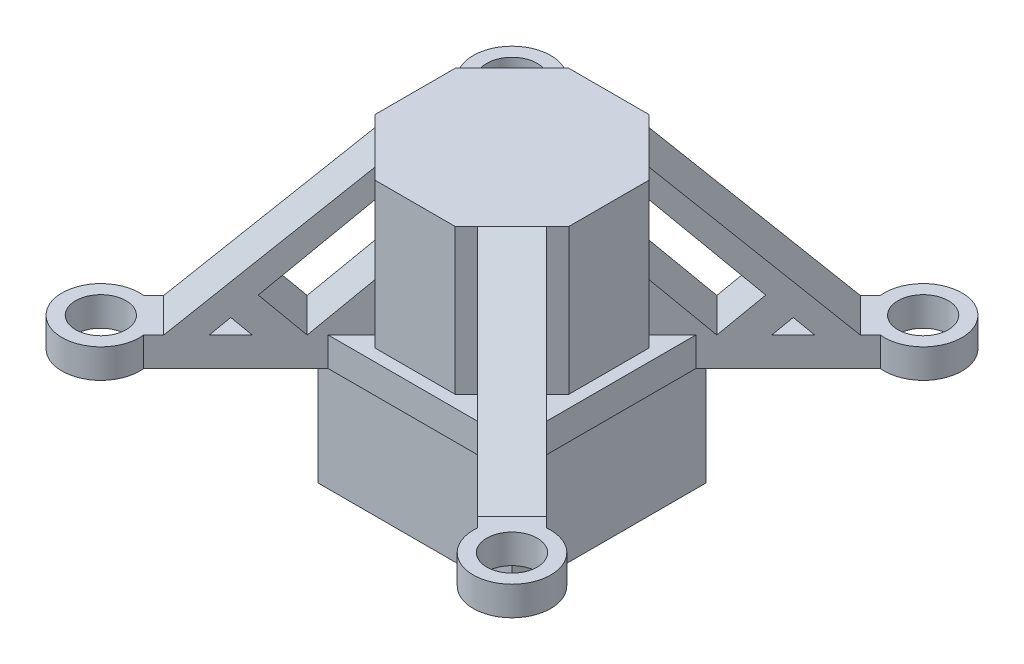
SolidWorks part; units mm, degrees
ref_plane "Front Plane" through (0, 0, 0) normal (0, 0, 1) x (1, 0, 0)
ref_plane "Top Plane" through (0, 0, 0) normal (0, 1, 0) x (1, 0, 0)
ref_plane "Right Plane" through (0, 0, 0) normal (1, 0, 0) x (0, 0, -1)
sketch "Sketch1" plane through (0, 0, 0) normal (0, 1, 0) x (1, 0, 0)
  line L1 (-10, 10) -> (10, 10)
  line L2 (-10, 10) -> (-10, -10)
  line L3 (-10, -10) -> (10, -10)
  line L4 (10, 10) -> (10, -10)
  line L5 (-10, 10) -> (10, -10) construction
  line L6 (-10, -10) -> (10, 10) construction
  point P0 (0, 0)
extrude "Boss-Extrude1" add sketch "Sketch1" against normal blind 12
sketch "Sketch2" plane through (0, 0, 0) normal (0, 1, 0) x (1, 0, 0)
  line L0 (7.7145, -11.25) -> (17.2375, -20.773)
  line L1 (11.25, 7.7145) -> (20.773, 17.2375)
  line L2 (7.7145, 11.25) -> (17.2375, 20.773)
  line L3 (11.25, -7.7145) -> (20.773, -17.2375)
  line L4 (-11.25, -7.7145) -> (-20.773, -17.2375)
  line L5 (-7.7145, -11.25) -> (-17.2375, -20.773)
  line L6 (-7.7145, 11.25) -> (-17.2375, 20.773)
  line L7 (-11.25, 7.7145) -> (-20.773, 17.2375)
  line L9 (-7.7145, -11.25) -> (7.7145, -11.25)
  line L10 (-11.25, -7.7145) -> (-11.25, 7.7145)
  line L11 (-7.7145, 11.25) -> (7.7145, 11.25)
  line L12 (11.25, -7.7145) -> (11.25, 7.7145)
  arc A0 (20.773, 17.2375) -> (17.2375, 20.773) centre (21.2132, 21.2132) ccw
  arc A1 (17.2375, -20.773) -> (20.773, -17.2375) centre (21.2132, -21.2132) ccw
  arc A2 (-20.773, -17.2375) -> (-17.2375, -20.773) centre (-21.2132, -21.2132) ccw
  arc A3 (-17.2375, 20.773) -> (-20.773, 17.2375) centre (-21.2132, 21.2132) ccw
  point P4 (0, 0)
  point P24 (0, 0)
  dimension "D1" = 4
extrude "Boss-Extrude2" add sketch "Sketch2" along normal blind 3
ref_plane "Plane1" through (0, 3, 0) normal (0, 1, 0) x (1, 0, 0)
sketch "Sketch3" plane through (0, 3, 0) normal (0, 1, 0) x (1, 0, 0)
  line L1 (10, 4.1421) -> (4.1421, 10)
  line L2 (4.1421, 10) -> (-4.1421, 10)
  line L3 (-4.1421, 10) -> (-10, 4.1421)
  line L4 (-10, 4.1421) -> (-10, -4.1421)
  line L5 (-10, -4.1421) -> (-4.1421, -10)
  line L6 (-4.1421, -10) -> (4.1421, -10)
  line L7 (4.1421, -10) -> (10, -4.1421)
  line L8 (10, -4.1421) -> (10, 4.1421)
  circle A0 centre (0, 0) radius 10 construction
extrude "Boss-Extrude3" add sketch "Sketch3" along normal blind 15
sketch "Sketch4" plane through (0, 3, 0) normal (0, 1, 0) x (1, 0, 0)
  line L0 (-11.25, -7.7145) -> (-19.7353, -16.1997)
  line L1 (-11.25, -7.7145) -> (-20.773, -17.2375) construction
  line L2 (-19.7353, -16.1997) -> (-16.1997, -19.7353)
  line L3 (-17.2375, -20.773) -> (-7.7145, -11.25) construction
  line L4 (-16.1997, -19.7353) -> (-7.7145, -11.25)
  line L5 (-7.7145, -11.25) -> (-5.3033, -8.8388)
  line L6 (-11.25, -7.7145) -> (-8.8388, -5.3033)
  line L7 (-7.7145, 11.25) -> (-16.1997, 19.7353)
  line L8 (-7.7145, 11.25) -> (-5.3033, 8.8388)
  line L9 (-19.7353, 16.1997) -> (-11.25, 7.7145)
  line L10 (-11.25, 7.7145) -> (-8.8388, 5.3033)
  line L11 (-16.1997, 19.7353) -> (-19.7353, 16.1997)
  line L12 (11.25, 7.7145) -> (19.7353, 16.1997)
  line L13 (11.25, 7.7145) -> (8.8388, 5.3033)
  line L14 (16.1997, 19.7353) -> (7.7145, 11.25)
  line L15 (7.7145, 11.25) -> (5.3033, 8.8388)
  line L16 (19.7353, 16.1997) -> (16.1997, 19.7353)
  line L17 (7.7145, -11.25) -> (16.1997, -19.7353)
  line L18 (7.7145, -11.25) -> (5.3033, -8.8388)
  line L19 (19.7353, -16.1997) -> (11.25, -7.7145)
  line L20 (11.25, -7.7145) -> (8.8388, -5.3033)
  line L21 (16.1997, -19.7353) -> (19.7353, -16.1997)
  line L22 (-8.8388, -5.3033) -> (-5.3033, -8.8388)
  line L23 (-5.3033, 8.8388) -> (-8.8388, 5.3033)
  line L24 (8.8388, 5.3033) -> (5.3033, 8.8388)
  line L25 (5.3033, -8.8388) -> (8.8388, -5.3033)
  point P33 (0, 0)
  point P42 (0, 0)
  dimension "D1" = 4
  dimension "D2" = 4
extrude "Boss-Extrude4" add sketch "Sketch4" along normal blind 15
move or copy body "Body-Move/Copy1" bodies to move or copy 104 copy no rotation origin (0, 0, 0) rotation axis (0, 1, 0) rotation angle 45
sketch "Sketch5" plane through (0, 0, 0) normal (0, 0, 1) x (1, 0, 0)
  line L0 (-25.4099, 18) -> (-10, 18)
  line L1 (-10, 18) -> (-25.4099, 3)
  line L2 (37.4, 3) -> (-37.4, 3) construction
  line L3 (-25.4099, 18) -> (-25.4099, 3) construction
  line L4 (-25.4099, 3) -> (-25.4099, 18)
  line L5 (0, -12) -> (0, 0) construction
  line L6 (10, 18) -> (25.4099, 3)
  line L7 (25.4099, 3) -> (25.4099, 18)
  line L8 (25.4099, 18) -> (10, 18)
extrude "Cut-Extrude2" cut sketch "Sketch5" against normal blind 15 and the other way blind 15
sketch "Sketch7" plane through (0, 0, 0) normal (1, 0, 0) x (0, 0, -1)
  line L0 (-25.4099, 18) -> (-10, 18)
  line L1 (-10, 18) -> (-25.4099, 3)
  line L4 (-25.4099, 3) -> (-25.4099, 18)
  line L6 (10, 18) -> (25.4099, 3)
  line L7 (25.4099, 3) -> (25.4099, 18)
  line L8 (25.4099, 18) -> (10, 18)
extrude "Cut-Extrude3" cut sketch "Sketch7" against normal blind 15 and the other way blind 15
sketch "Sketch8" plane through (2.5, 0, 0) normal (1, 0, 0) x (0, 0, -1)
  line L2 (37.4, 3) -> (-37.4, 3) construction
  line L4 (-10, 18) -> (-10, 3) construction
  line L5 (-10, 7.9447) -> (-10, 15.0849)
  line L7 (-10, 15.0849) -> (-18.5148, 6.5701)
  line L10 (-18.9558, 3) -> (-22.0849, 3)
  line L11 (-20.6742, 4.4107) -> (-22.0849, 3)
  line L12 (-14.9447, 3) -> (-18.5148, 6.5701)
  line L13 (-18.9558, 3) -> (-20.5203, 4.5645)
  line L14 (-20.6742, 4.4107) -> (-20.5203, 4.5645)
  line L15 (-14.9447, 3) -> (-10, 7.9447)
  line L16 (0, -12) -> (0, 0) construction
  line L17 (14.9447, 3) -> (10, 7.9447)
  line L18 (20.6742, 4.4107) -> (20.5203, 4.5645)
  line L19 (18.9558, 3) -> (20.5203, 4.5645)
  line L20 (14.9447, 3) -> (18.5148, 6.5701)
  line L21 (20.6742, 4.4107) -> (22.0849, 3)
  line L22 (18.9558, 3) -> (22.0849, 3)
  line L23 (10, 15.0849) -> (18.5148, 6.5701)
  line L24 (10, 7.9447) -> (10, 15.0849)
extrude "Cut-Extrude4" cut sketch "Sketch8" against normal blind 15 and the other way blind 15
sketch "Sketch9" plane through (0, 0, 0) normal (0, 0, 1) x (1, 0, 0)
  line L5 (-10, 7.9447) -> (-10, 15.0849)
  line L7 (-10, 15.0849) -> (-18.5148, 6.5701)
  line L10 (-18.9558, 3) -> (-22.0849, 3)
  line L11 (-20.6742, 4.4107) -> (-22.0849, 3)
  line L12 (-14.9447, 3) -> (-18.5148, 6.5701)
  line L13 (-18.9558, 3) -> (-20.5203, 4.5645)
  line L14 (-20.6742, 4.4107) -> (-20.5203, 4.5645)
  line L15 (-14.9447, 3) -> (-10, 7.9447)
  line L17 (14.9447, 3) -> (10, 7.9447)
  line L18 (20.6742, 4.4107) -> (20.5203, 4.5645)
  line L19 (18.9558, 3) -> (20.5203, 4.5645)
  line L20 (14.9447, 3) -> (18.5148, 6.5701)
  line L21 (20.6742, 4.4107) -> (22.0849, 3)
  line L22 (18.9558, 3) -> (22.0849, 3)
  line L23 (10, 15.0849) -> (18.5148, 6.5701)
  line L24 (10, 7.9447) -> (10, 15.0849)
extrude "Cut-Extrude5" cut sketch "Sketch9" against normal blind 15 and the other way blind 15
sketch "Sketch10" plane through (0, 0, 0) normal (0, 1, 0) x (1, 0, 0)
  circle A0 centre (0, -30) radius 2.6
  circle A1 centre (-30, 0) radius 2.6
  circle A2 centre (0, 30) radius 2.6
  circle A3 centre (30, 0) radius 2.6
  point P12 (0, 0)
  dimension "D1" = 4
extrude "Cut-Extrude6" cut sketch "Sketch10" along normal blind 25
move or copy body "Body-Move/Copy2" bodies to move or copy 111 copy no rotation origin (0, 0, 0) rotation axis (0, 1, 0) rotation angle 45
